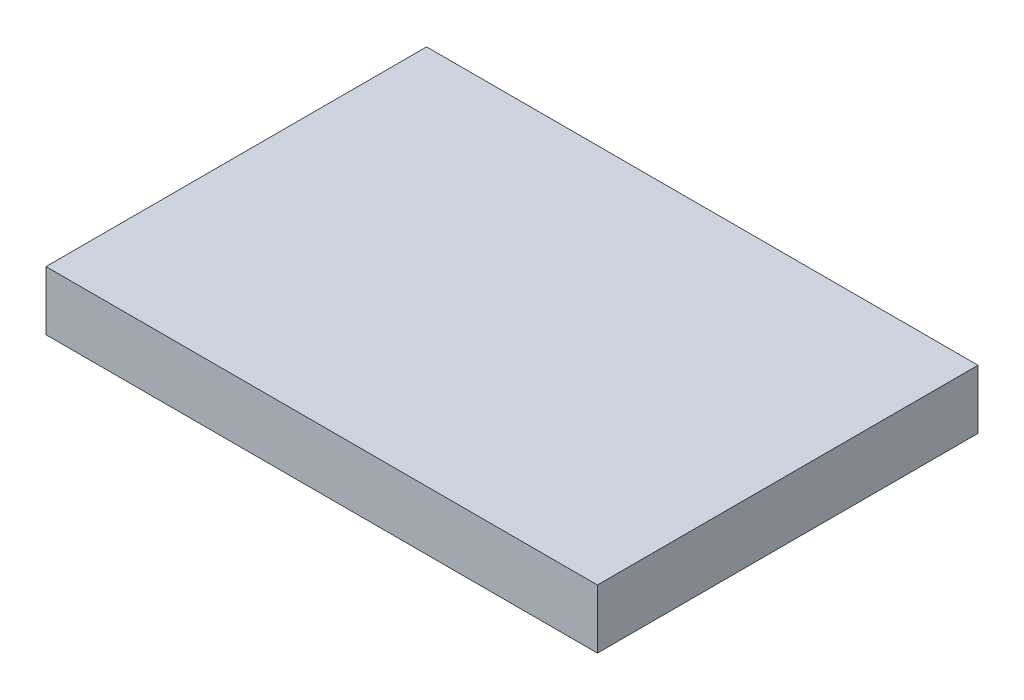
SolidWorks part; units mm, degrees
ref_plane "Спереди" through (0, 0, 0) normal (0, 0, 1) x (1, 0, 0)
ref_plane "Сверху" through (0, 0, 0) normal (0, 1, 0) x (1, 0, 0)
ref_plane "Справа" through (0, 0, 0) normal (1, 0, 0) x (0, 0, -1)
sketch "Эскиз1" plane through (0, 0, 0) normal (0, 1, 0) x (1, 0, 0)
  line L1 (0, 0) -> (35.5, 0)
  line L2 (0, 0) -> (0, -24.5)
  line L3 (0, -24.5) -> (35.5, -24.5)
  line L4 (35.5, 0) -> (35.5, -24.5)
  dimension "D1" = 24.5
  dimension "D2" = 35.5
extrude "Бобышка-Вытянуть1" add sketch "Эскиз1" along normal blind 3.8
